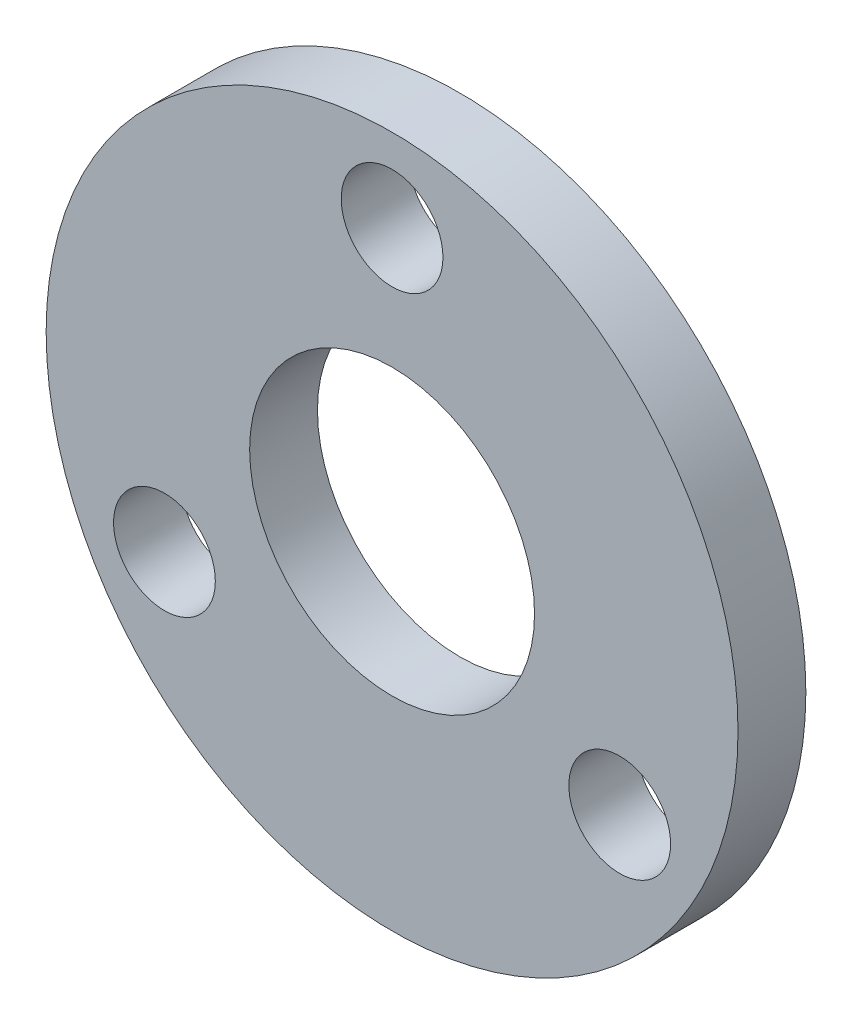
SolidWorks part; units mm, degrees
ref_plane "Front Plane" through (0, 0, 0) normal (0, 0, 1) x (1, 0, 0)
ref_plane "Top Plane" through (0, 0, 0) normal (0, 1, 0) x (1, 0, 0)
ref_plane "Right Plane" through (0, 0, 0) normal (1, 0, 0) x (0, 0, -1)
sketch "Эскиз1" plane through (0, 0, 0) normal (0, 0, 1) x (1, 0, 0)
  circle A0 centre (0, 0) radius 10.2
  circle A1 centre (0, 0) radius 7.75 construction
  circle A2 centre (-6.7117, -3.875) radius 1.5
  circle A3 centre (0, 7.75) radius 1.5
  circle A4 centre (6.7117, -3.875) radius 1.5
  circle A5 centre (0, 0) radius 4.2
  dimension "D1" = 20.4
  dimension "D2" = 15.5
  dimension "D3" = 3
  dimension "D5" = 8.4
  dimension "D4" = 3
extrude "Бобышка-Вытянуть1" add sketch "Эскиз1" along normal mid plane 2
